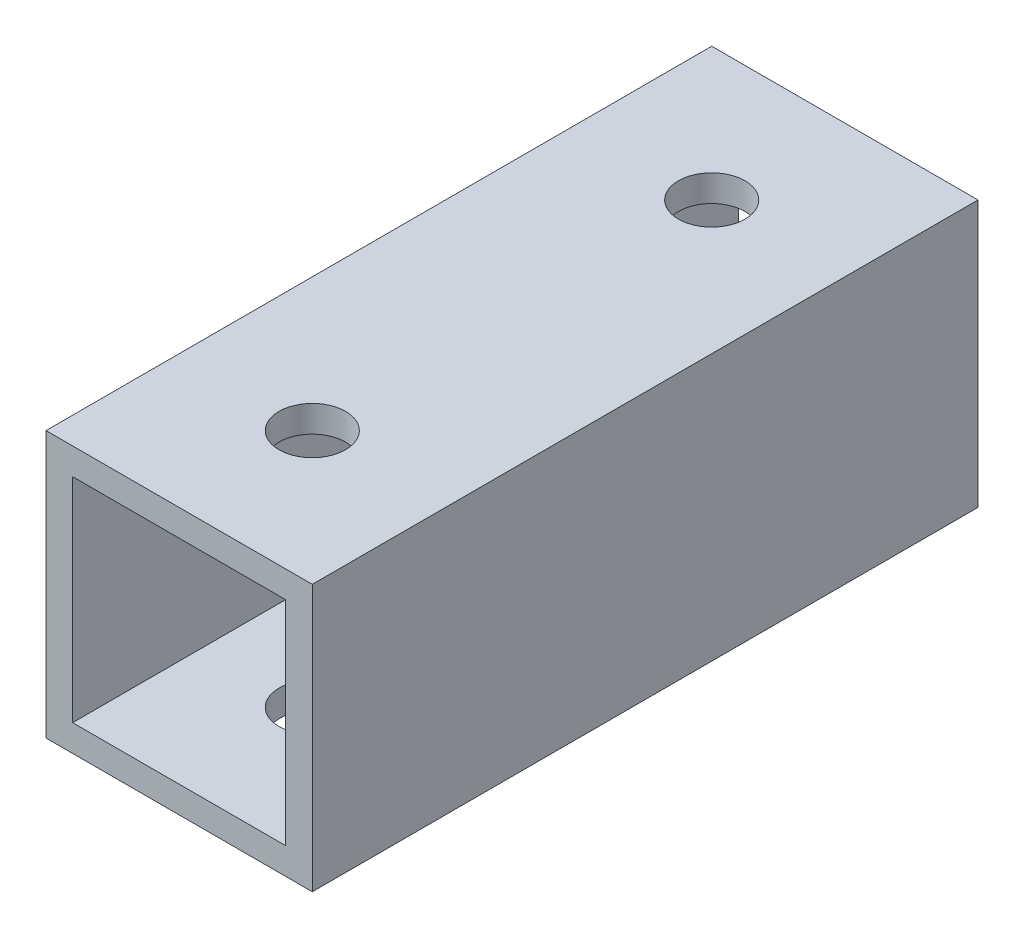
SolidWorks part; units mm, degrees
ref_plane "前视基准面" through (0, 0, 0) normal (0, 0, 1) x (1, 0, 0)
ref_plane "上视基准面" through (0, 0, 0) normal (0, 1, 0) x (1, 0, 0)
ref_plane "右视基准面" through (0, 0, 0) normal (1, 0, 0) x (0, 0, -1)
other "Configuration Table"
sketch "草图1" plane through (0, 0, 0) normal (0, 0, 1) x (1, 0, 0)
  line L1 (-10, -10) -> (10, -10)
  line L2 (-10, -10) -> (-10, 10)
  line L3 (-10, 10) -> (10, 10)
  line L4 (10, -10) -> (10, 10)
  line L5 (-10, -10) -> (10, 10) construction
  line L6 (-10, 10) -> (10, -10) construction
  line L7 (-8, -8) -> (8, -8)
  line L8 (-8, -8) -> (-8, 8)
  line L9 (-8, 8) -> (8, 8)
  line L10 (8, -8) -> (8, 8)
  line L11 (-8, -8) -> (8, 8) construction
  line L12 (-8, 8) -> (8, -8) construction
  point P0 (0, 0)
  point P6 (0, 0)
  dimension "D1" = 20
  dimension "D2" = 20
  dimension "D3" = 2
  dimension "D4" = 2
extrude "凸台-拉伸1" add sketch "草图1" along normal blind 50
sketch "草图2" plane through (0, 10, 0) normal (0, 1, 0) x (1, 0, 0)
  line L0 (0, 0) -> (0, -50) construction
  line L1 (10, -50) -> (-10, -50) construction
  line L4 (10, 0) -> (-10, 0) construction
  circle A0 centre (0, -10) radius 2.5
  circle A1 centre (0, -40) radius 2.5
  dimension "D1" = 30
  dimension "D3" = 5
  dimension "D2" = 10
extrude "切除-拉伸1" cut sketch "草图2" against normal up to surface (20 mm away) up to face at (0, -10, 25)
